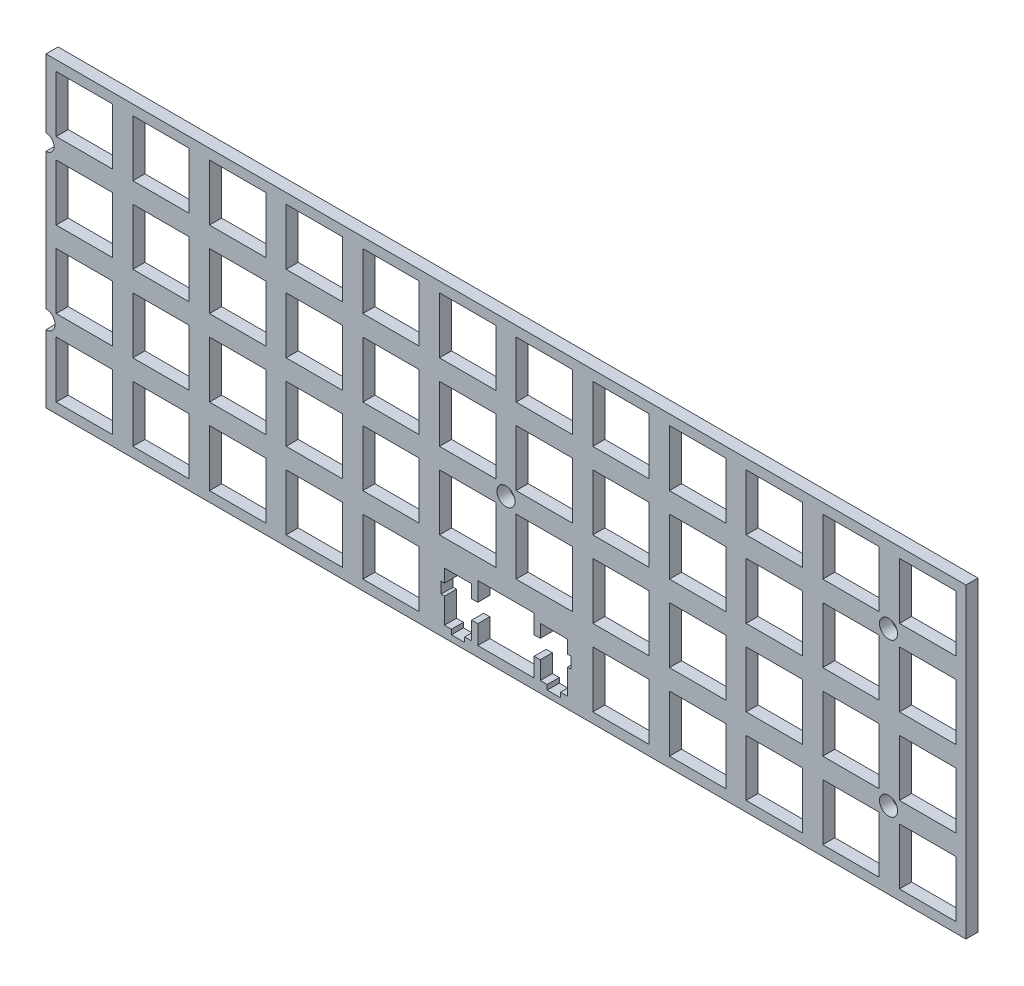
SolidWorks part; units mm, degrees
material "EPDM 60 Durometer"
ref_plane "Front Plane" through (0, 0, 0) normal (0, 0, 1) x (1, 0, 0)
ref_plane "Top Plane" through (0, 0, 0) normal (0, 1, 0) x (1, 0, 0)
ref_plane "Right Plane" through (0, 0, 0) normal (1, 0, 0) x (0, 0, -1)
sketch "Model" plane through (0, 0, 0) normal (0, 0, 1) x (1, 0, 0)
  line L0 (0.0951, 76.4575) -> (228.695, 76.4575)
  line L1 (228.695, 76.4575) -> (228.695, 0.2577)
  line L2 (228.695, 0.2577) -> (0.0951, 0.2577)
  line L3 (0.0951, 0.2577) -> (0.0951, 76.4575)
  line L4 (107.395, 16.7831) -> (107.395, 12.0826)
  line L5 (107.395, 12.0826) -> (105.869, 12.0826)
  line L6 (105.869, 12.0826) -> (105.869, 15.3128)
  line L7 (105.869, 15.3128) -> (99.1182, 15.3128)
  line L8 (99.1182, 15.3128) -> (99.1182, 12.0826)
  line L9 (99.1182, 12.0826) -> (98.2941, 12.0826)
  line L10 (98.2941, 12.0826) -> (98.2941, 9.2838)
  line L11 (98.2941, 9.2838) -> (99.1182, 9.2838)
  line L12 (99.1182, 9.2838) -> (99.1182, 3.0138)
  line L13 (99.1182, 3.0138) -> (100.845, 3.0138)
  line L14 (100.845, 3.0138) -> (100.845, 1.8135)
  line L15 (100.845, 1.8135) -> (104.144, 1.8135)
  line L16 (104.144, 1.8135) -> (104.144, 3.0138)
  line L17 (104.144, 3.0138) -> (105.869, 3.0138)
  line L18 (105.869, 3.0138) -> (105.869, 7.4827)
  line L19 (105.869, 7.4827) -> (107.395, 7.4827)
  line L20 (107.395, 7.4827) -> (107.395, 2.7836)
  line L21 (107.395, 2.7836) -> (121.394, 2.7836)
  line L22 (121.394, 2.7836) -> (121.394, 7.4827)
  line L23 (121.394, 7.4827) -> (122.92, 7.4827)
  line L24 (122.92, 7.4827) -> (122.92, 3.0138)
  line L25 (122.92, 3.0138) -> (124.645, 3.0138)
  line L26 (124.645, 3.0138) -> (124.645, 1.8135)
  line L27 (124.645, 1.8135) -> (127.944, 1.8135)
  line L28 (127.944, 1.8135) -> (127.944, 3.0138)
  line L29 (127.944, 3.0138) -> (129.669, 3.0138)
  line L30 (129.669, 3.0138) -> (129.669, 9.2838)
  line L31 (129.669, 9.2838) -> (130.495, 9.2838)
  line L32 (130.495, 9.2838) -> (130.495, 12.0826)
  line L33 (130.495, 12.0826) -> (129.669, 12.0826)
  line L34 (129.669, 12.0826) -> (129.669, 15.3128)
  line L35 (129.669, 15.3128) -> (122.92, 15.3128)
  line L36 (122.92, 15.3128) -> (122.92, 12.0826)
  line L37 (122.92, 12.0826) -> (121.394, 12.0826)
  line L38 (121.394, 12.0826) -> (121.394, 16.7831)
  line L39 (121.394, 16.7831) -> (107.395, 16.7831)
  line L40 (2.6197, 16.7831) -> (16.6192, 16.7831)
  line L41 (16.6192, 16.7831) -> (16.6192, 2.7836)
  line L42 (16.6192, 2.7836) -> (2.6197, 2.7836)
  line L43 (2.6197, 2.7836) -> (2.6197, 16.7831)
  line L44 (21.6697, 16.7831) -> (35.669, 16.7831)
  line L45 (35.669, 16.7831) -> (35.669, 2.7836)
  line L46 (35.669, 2.7836) -> (21.6697, 2.7836)
  line L47 (21.6697, 2.7836) -> (21.6697, 16.7831)
  line L48 (40.7197, 16.7831) -> (54.719, 16.7831)
  line L49 (54.719, 16.7831) -> (54.719, 2.7836)
  line L50 (54.719, 2.7836) -> (40.7197, 2.7836)
  line L51 (40.7197, 2.7836) -> (40.7197, 16.7831)
  line L52 (59.7697, 16.7831) -> (73.769, 16.7831)
  line L53 (73.769, 16.7831) -> (73.769, 2.7836)
  line L54 (73.769, 2.7836) -> (59.7697, 2.7836)
  line L55 (59.7697, 2.7836) -> (59.7697, 16.7831)
  line L56 (78.8197, 16.7831) -> (92.819, 16.7831)
  line L57 (92.819, 16.7831) -> (92.819, 2.7836)
  line L58 (92.819, 2.7836) -> (78.8197, 2.7836)
  line L59 (78.8197, 2.7836) -> (78.8197, 16.7831)
  line L60 (135.97, 16.7831) -> (149.969, 16.7831)
  line L61 (149.969, 16.7831) -> (149.969, 2.7836)
  line L62 (149.969, 2.7836) -> (135.97, 2.7836)
  line L63 (135.97, 2.7836) -> (135.97, 16.7831)
  line L64 (155.02, 16.7831) -> (169.019, 16.7831)
  line L65 (169.019, 16.7831) -> (169.019, 2.7836)
  line L66 (169.019, 2.7836) -> (155.02, 2.7836)
  line L67 (155.02, 2.7836) -> (155.02, 16.7831)
  line L68 (174.07, 16.7831) -> (188.069, 16.7831)
  line L69 (188.069, 16.7831) -> (188.069, 2.7836)
  line L70 (188.069, 2.7836) -> (174.07, 2.7836)
  line L71 (174.07, 2.7836) -> (174.07, 16.7831)
  line L72 (193.12, 16.7831) -> (207.119, 16.7831)
  line L73 (207.119, 16.7831) -> (207.119, 2.7836)
  line L74 (207.119, 2.7836) -> (193.12, 2.7836)
  line L75 (193.12, 2.7836) -> (193.12, 16.7831)
  line L76 (212.17, 16.7831) -> (226.169, 16.7831)
  line L77 (226.169, 16.7831) -> (226.169, 2.7836)
  line L78 (226.169, 2.7836) -> (212.17, 2.7836)
  line L79 (212.17, 2.7836) -> (212.17, 16.7831)
  line L80 (2.6197, 35.833) -> (16.6192, 35.833)
  line L81 (16.6192, 35.833) -> (16.6192, 21.8336)
  line L82 (16.6192, 21.8336) -> (2.6197, 21.8336)
  line L83 (2.6197, 21.8336) -> (2.6197, 35.833)
  line L84 (21.6697, 35.833) -> (35.669, 35.833)
  line L85 (35.669, 35.833) -> (35.669, 21.8336)
  line L86 (35.669, 21.8336) -> (21.6697, 21.8336)
  line L87 (21.6697, 21.8336) -> (21.6697, 35.833)
  line L88 (40.7197, 35.833) -> (54.719, 35.833)
  line L89 (54.719, 35.833) -> (54.719, 21.8336)
  line L90 (54.719, 21.8336) -> (40.7197, 21.8336)
  line L91 (40.7197, 21.8336) -> (40.7197, 35.833)
  line L92 (59.7697, 35.833) -> (73.769, 35.833)
  line L93 (73.769, 35.833) -> (73.769, 21.8336)
  line L94 (73.769, 21.8336) -> (59.7697, 21.8336)
  line L95 (59.7697, 21.8336) -> (59.7697, 35.833)
  line L96 (78.8197, 35.833) -> (92.819, 35.833)
  line L97 (92.819, 35.833) -> (92.819, 21.8336)
  line L98 (92.819, 21.8336) -> (78.8197, 21.8336)
  line L99 (78.8197, 21.8336) -> (78.8197, 35.833)
  line L100 (97.8683, 35.833) -> (111.869, 35.833)
  line L101 (111.869, 35.833) -> (111.869, 21.8336)
  line L102 (111.869, 21.8336) -> (97.8683, 21.8336)
  line L103 (97.8683, 21.8336) -> (97.8683, 35.833)
  line L104 (116.918, 35.833) -> (130.919, 35.833)
  line L105 (130.919, 35.833) -> (130.919, 21.8336)
  line L106 (130.919, 21.8336) -> (116.918, 21.8336)
  line L107 (116.918, 21.8336) -> (116.918, 35.833)
  line L108 (135.97, 35.833) -> (149.969, 35.833)
  line L109 (149.969, 35.833) -> (149.969, 21.8336)
  line L110 (149.969, 21.8336) -> (135.97, 21.8336)
  line L111 (135.97, 21.8336) -> (135.97, 35.833)
  line L112 (155.02, 35.833) -> (169.019, 35.833)
  line L113 (169.019, 35.833) -> (169.019, 21.8336)
  line L114 (169.019, 21.8336) -> (155.02, 21.8336)
  line L115 (155.02, 21.8336) -> (155.02, 35.833)
  line L116 (174.07, 35.833) -> (188.069, 35.833)
  line L117 (188.069, 35.833) -> (188.069, 21.8336)
  line L118 (188.069, 21.8336) -> (174.07, 21.8336)
  line L119 (174.07, 21.8336) -> (174.07, 35.833)
  line L120 (193.12, 35.833) -> (207.119, 35.833)
  line L121 (207.119, 35.833) -> (207.119, 21.8336)
  line L122 (207.119, 21.8336) -> (193.12, 21.8336)
  line L123 (193.12, 21.8336) -> (193.12, 35.833)
  line L124 (212.17, 35.833) -> (226.169, 35.833)
  line L125 (226.169, 35.833) -> (226.169, 21.8336)
  line L126 (226.169, 21.8336) -> (212.17, 21.8336)
  line L127 (212.17, 21.8336) -> (212.17, 35.833)
  line L128 (2.6197, 54.8831) -> (16.6192, 54.8831)
  line L129 (16.6192, 54.8831) -> (16.6192, 40.8838)
  line L130 (16.6192, 40.8838) -> (2.6197, 40.8838)
  line L131 (2.6197, 40.8838) -> (2.6197, 54.8831)
  line L132 (21.6697, 54.8831) -> (35.669, 54.8831)
  line L133 (35.669, 54.8831) -> (35.669, 40.8838)
  line L134 (35.669, 40.8838) -> (21.6697, 40.8838)
  line L135 (21.6697, 40.8838) -> (21.6697, 54.8831)
  line L136 (40.7197, 54.8831) -> (54.719, 54.8831)
  line L137 (54.719, 54.8831) -> (54.719, 40.8838)
  line L138 (54.719, 40.8838) -> (40.7197, 40.8838)
  line L139 (40.7197, 40.8838) -> (40.7197, 54.8831)
  line L140 (59.7697, 54.8831) -> (73.769, 54.8831)
  line L141 (73.769, 54.8831) -> (73.769, 40.8838)
  line L142 (73.769, 40.8838) -> (59.7697, 40.8838)
  line L143 (59.7697, 40.8838) -> (59.7697, 54.8831)
  line L144 (78.8197, 54.8831) -> (92.819, 54.8831)
  line L145 (92.819, 54.8831) -> (92.819, 40.8838)
  line L146 (92.819, 40.8838) -> (78.8197, 40.8838)
  line L147 (78.8197, 40.8838) -> (78.8197, 54.8831)
  line L148 (97.8683, 54.8831) -> (111.869, 54.8831)
  line L149 (111.869, 54.8831) -> (111.869, 40.8838)
  line L150 (111.869, 40.8838) -> (97.8683, 40.8838)
  line L151 (97.8683, 40.8838) -> (97.8683, 54.8831)
  line L152 (116.918, 54.8831) -> (130.919, 54.8831)
  line L153 (130.919, 54.8831) -> (130.919, 40.8838)
  line L154 (130.919, 40.8838) -> (116.918, 40.8838)
  line L155 (116.918, 40.8838) -> (116.918, 54.8831)
  line L156 (135.97, 54.8831) -> (149.969, 54.8831)
  line L157 (149.969, 54.8831) -> (149.969, 40.8838)
  line L158 (149.969, 40.8838) -> (135.97, 40.8838)
  line L159 (135.97, 40.8838) -> (135.97, 54.8831)
  line L160 (155.02, 54.8831) -> (169.019, 54.8831)
  line L161 (169.019, 54.8831) -> (169.019, 40.8838)
  line L162 (169.019, 40.8838) -> (155.02, 40.8838)
  line L163 (155.02, 40.8838) -> (155.02, 54.8831)
  line L164 (174.07, 54.8831) -> (188.069, 54.8831)
  line L165 (188.069, 54.8831) -> (188.069, 40.8838)
  line L166 (188.069, 40.8838) -> (174.07, 40.8838)
  line L167 (174.07, 40.8838) -> (174.07, 54.8831)
  line L168 (193.12, 54.8831) -> (207.119, 54.8831)
  line L169 (207.119, 54.8831) -> (207.119, 40.8838)
  line L170 (207.119, 40.8838) -> (193.12, 40.8838)
  line L171 (193.12, 40.8838) -> (193.12, 54.8831)
  line L172 (212.17, 54.8831) -> (226.169, 54.8831)
  line L173 (226.169, 54.8831) -> (226.169, 40.8838)
  line L174 (226.169, 40.8838) -> (212.17, 40.8838)
  line L175 (212.17, 40.8838) -> (212.17, 54.8831)
  line L176 (2.6197, 73.9331) -> (16.6192, 73.9331)
  line L177 (16.6192, 73.9331) -> (16.6192, 59.9338)
  line L178 (16.6192, 59.9338) -> (2.6197, 59.9338)
  line L179 (2.6197, 59.9338) -> (2.6197, 73.9331)
  line L180 (21.6697, 73.9331) -> (35.669, 73.9331)
  line L181 (35.669, 73.9331) -> (35.669, 59.9338)
  line L182 (35.669, 59.9338) -> (21.6697, 59.9338)
  line L183 (21.6697, 59.9338) -> (21.6697, 73.9331)
  line L184 (40.7197, 73.9331) -> (54.719, 73.9331)
  line L185 (54.719, 73.9331) -> (54.719, 59.9338)
  line L186 (54.719, 59.9338) -> (40.7197, 59.9338)
  line L187 (40.7197, 59.9338) -> (40.7197, 73.9331)
  line L188 (59.7697, 73.9331) -> (73.769, 73.9331)
  line L189 (73.769, 73.9331) -> (73.769, 59.9338)
  line L190 (73.769, 59.9338) -> (59.7697, 59.9338)
  line L191 (59.7697, 59.9338) -> (59.7697, 73.9331)
  line L192 (78.8197, 73.9331) -> (92.819, 73.9331)
  line L193 (92.819, 73.9331) -> (92.819, 59.9338)
  line L194 (92.819, 59.9338) -> (78.8197, 59.9338)
  line L195 (78.8197, 59.9338) -> (78.8197, 73.9331)
  line L196 (97.8683, 73.9331) -> (111.869, 73.9331)
  line L197 (111.869, 73.9331) -> (111.869, 59.9338)
  line L198 (111.869, 59.9338) -> (97.8683, 59.9338)
  line L199 (97.8683, 59.9338) -> (97.8683, 73.9331)
  line L200 (116.918, 73.9331) -> (130.919, 73.9331)
  line L201 (130.919, 73.9331) -> (130.919, 59.9338)
  line L202 (130.919, 59.9338) -> (116.918, 59.9338)
  line L203 (116.918, 59.9338) -> (116.918, 73.9331)
  line L204 (135.97, 73.9331) -> (149.969, 73.9331)
  line L205 (149.969, 73.9331) -> (149.969, 59.9338)
  line L206 (149.969, 59.9338) -> (135.97, 59.9338)
  line L207 (135.97, 59.9338) -> (135.97, 73.9331)
  line L208 (155.02, 73.9331) -> (169.019, 73.9331)
  line L209 (169.019, 73.9331) -> (169.019, 59.9338)
  line L210 (169.019, 59.9338) -> (155.02, 59.9338)
  line L211 (155.02, 59.9338) -> (155.02, 73.9331)
  line L212 (174.07, 73.9331) -> (188.069, 73.9331)
  line L213 (188.069, 73.9331) -> (188.069, 59.9338)
  line L214 (188.069, 59.9338) -> (174.07, 59.9338)
  line L215 (174.07, 59.9338) -> (174.07, 73.9331)
  line L216 (193.12, 73.9331) -> (207.119, 73.9331)
  line L217 (207.119, 73.9331) -> (207.119, 59.9338)
  line L218 (207.119, 59.9338) -> (193.12, 59.9338)
  line L219 (193.12, 59.9338) -> (193.12, 73.9331)
  line L220 (212.17, 73.9331) -> (226.169, 73.9331)
  line L221 (226.169, 73.9331) -> (226.169, 59.9338)
  line L222 (226.169, 59.9338) -> (212.17, 59.9338)
  line L223 (212.17, 59.9338) -> (212.17, 73.9331)
extrude "Boss-Extrude1" add sketch "Model" along normal blind 3
sketch "Sketch1" plane through (0, 0, 3) normal (0, 0, 1) x (1, 0, 0)
  line L0 (0.094, 59.4503) -> (0.0944, 55.5003)
  circle A0 centre (114.394, 38.4003) radius 2.25 construction
  circle A1 centre (114.394, 38.4003) radius 2.25
  circle A2 centre (209.464, 19.3503) radius 2.25 construction
  circle A3 centre (209.464, 57.4503) radius 2.25 construction
  circle A4 centre (209.464, 19.3503) radius 2.25
  circle A5 centre (209.464, 57.4503) radius 2.25
  arc A6 (0.0944, 55.5003) -> (0.094, 59.4503) centre (0.1115, 57.4753) ccw construction
  arc A7 (0.0944, 55.5003) -> (0.094, 59.4503) centre (0.1115, 57.4753) ccw
  circle A8 centre (0.094, 19.3503) radius 2.25 construction
  circle A9 centre (0.094, 19.3503) radius 2.25
extrude "Cut-Extrude1" cut sketch "Sketch1" against normal through all
